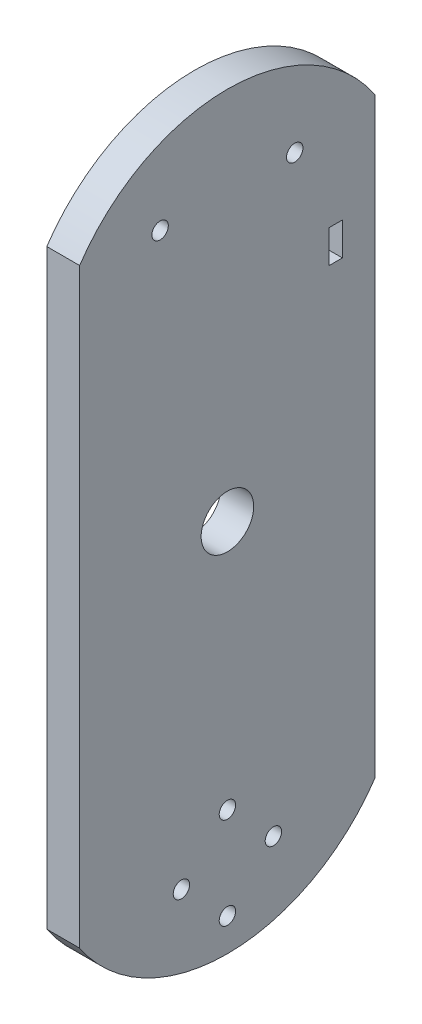
SolidWorks part; units mm, degrees
ref_plane "Front Plane" through (0, 0, 0) normal (0, 0, 1) x (1, 0, 0)
ref_plane "Top Plane" through (0, 0, 0) normal (0, 1, 0) x (1, 0, 0)
ref_plane "Right Plane" through (0, 0, 0) normal (1, 0, 0) x (0, 0, -1)
sketch "Sketch1" plane through (0, 0, 0) normal (1, 0, 0) x (0, 0, -1)
  line L0 (-10.9076, 0) -> (34.9043, 0) construction
  line L1 (0, 8.3106) -> (0, -10.0667) construction
  line L4 (-25.9471, -12) -> (30.0563, -12) construction
  line L5 (-20.6931, 45) -> (25.4325, 45) construction
  line L6 (-22.5, 0) -> (-22.5, 90)
  line L7 (22.5, 0) -> (22.5, 90)
  line L9 (15.5, 76) -> (17.5, 76)
  line L10 (15.5, 76) -> (15.5, 71)
  line L11 (15.5, 71) -> (17.5, 71)
  line L12 (17.5, 76) -> (17.5, 71)
  circle A0 centre (0, 0) radius 7 construction
  circle A1 centre (0, 7) radius 1.25
  circle A2 centre (7, 0) radius 1.25
  circle A3 centre (0, -7) radius 1.25
  circle A4 centre (-7, 0) radius 1.25
  circle A7 centre (-10.25, 88.5) radius 1.25
  circle A8 centre (10.25, 88.5) radius 1.25
  circle A9 centre (0, 45) radius 4
  arc A10 (-22.5, 0) -> (22.5, 0) centre (0, 15.0937) ccw
  arc A11 (-22.5, 90) -> (22.5, 90) centre (0, 74.9063) cw
  point P7 (7, 0)
  point P8 (0, 7)
  point P9 (0, -7)
  point P10 (-7, 0)
  dimension "D1" = 14
  dimension "D2" = 2.5
  dimension "D3" = 22.5
  dimension "D4" = 22.5
  dimension "D6" = 2.5
  dimension "D10" = 8
  dimension "D5" = 90
  dimension "D7" = 20.5
  dimension "D8" = 10.25
  dimension "D9" = 45
  dimension "D11" = 12
  dimension "D12" = 43.5
  dimension "D13" = 5
  dimension "D14" = 2
  dimension "D15" = 5
  dimension "D16" = 12.5
extrude "Boss-Extrude1" add sketch "Sketch1" along normal blind 5
